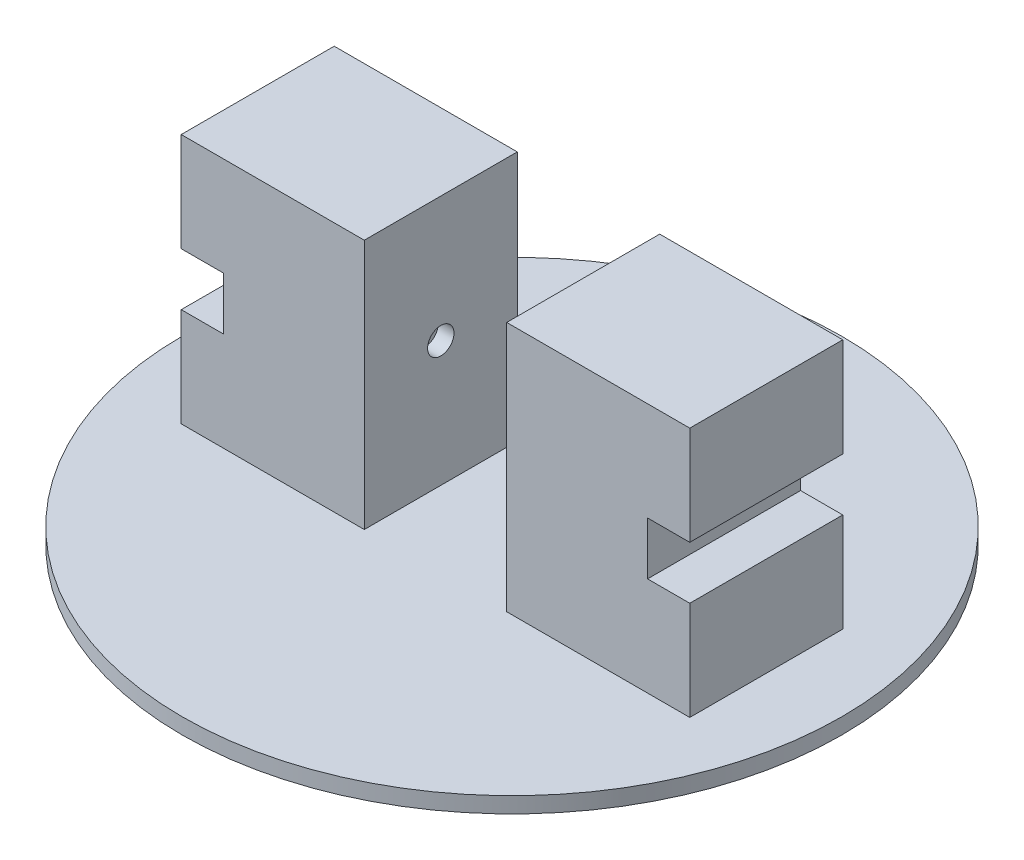
SolidWorks part; units mm, degrees
ref_plane "前视基准面" through (0, 0, 0) normal (0, 0, 1) x (1, 0, 0)
ref_plane "上视基准面" through (0, 0, 0) normal (0, 1, 0) x (1, 0, 0)
ref_plane "右视基准面" through (0, 0, 0) normal (1, 0, 0) x (0, 0, -1)
sketch "草图1" plane through (0, 0, 0) normal (0, 0, 1) x (1, 0, 0)
  line L1 (0, 0) -> (34.7, 0)
  line L2 (0, 0) -> (0, 47.5)
  line L3 (0, 47.5) -> (34.7, 47.5)
  line L4 (34.7, 0) -> (34.7, 47.5)
  line L5 (-27, 0) -> (-61.7, 0)
  line L6 (-27, 0) -> (-27, 47.5)
  line L7 (-27, 47.5) -> (-61.7, 47.5)
  line L8 (-61.7, 0) -> (-61.7, 47.5)
  dimension "D1" = 34.7
  dimension "D2" = 47.5
  dimension "D3" = 27
extrude "凸台-拉伸1" add sketch "草图1" along normal blind 29
sketch "草图2" plane through (34.7, 0, 0) normal (1, 0, 0) x (0, 0, -1)
  line L0 (-29, 23.75) -> (0, 23.75) construction
  line L1 (-29, 0) -> (-29, 47.5) construction
  line L2 (0, 0) -> (0, 47.5) construction
  line L3 (0, 23.75) -> (-29, 23.75) construction
  line L4 (-29, 28.75) -> (0, 28.75)
  line L5 (-29, 28.75) -> (-29, 18.75)
  line L6 (-29, 18.75) -> (0, 18.75)
  line L7 (0, 28.75) -> (0, 18.75)
  dimension "D1" = 10
extrude "切除-拉伸1" cut sketch "草图2" against normal blind 8
sketch "草图3" plane through (-61.7, 0, 0) normal (-1, 0, 0) x (0, 0, 1)
  line L0 (0, 23.75) -> (29, 23.75) construction
  line L1 (0, 47.5) -> (0, 0) construction
  line L2 (29, 47.5) -> (29, 0) construction
  line L3 (29, 23.75) -> (0, 23.75) construction
  line L4 (0, 28.75) -> (29, 28.75)
  line L5 (0, 28.75) -> (0, 18.75)
  line L6 (0, 18.75) -> (29, 18.75)
  line L7 (29, 28.75) -> (29, 18.75)
  dimension "D1" = 10
extrude "切除-拉伸2" cut sketch "草图3" against normal blind 8
sketch "草图4" plane through (0, 0, 0) normal (0, -1, 0) x (1, 0, 0)
  line L0 (-27, 14.5) -> (0, 14.5) construction
  line L1 (-27, 29) -> (-27, 0) construction
  line L2 (0, 29) -> (0, 0) construction
  line L3 (-13.5, 14.5) -> (-13.5, 33.9219) construction
  circle A0 centre (-13.5, 14.5) radius 62.5
  dimension "D1" = 125
extrude "凸台-拉伸2" add sketch "草图4" along normal blind 3
sketch "草图5" plane through (-27, 0, 0) normal (1, 0, 0) x (0, 0, -1)
  line L0 (-14.5, 47.5) -> (-14.5, 0) construction
  line L1 (-29, 47.5) -> (0, 47.5) construction
  line L2 (48, 0) -> (-77, 0) construction
  line L3 (0, 23.75) -> (-29, 23.75) construction
  line L4 (0, 18.75) -> (0, 28.75) construction
  line L5 (-29, 28.75) -> (-29, 18.75) construction
  circle A0 centre (-14.5, 23.75) radius 2.5
  dimension "D1" = 5
extrude "切除-拉伸3" cut sketch "草图5" against normal blind 3 and the other way blind 22
sketch "草图6" plane through (0, 0, 0) normal (-1, 0, 0) x (0, 0, 1)
  line L0 (14.5, 47.5) -> (14.5, 6.5115) construction
  line L1 (29, 47.5) -> (0, 47.5) construction
  line L2 (29, 23.75) -> (6.0356, 23.75)
  line L3 (29, 18.75) -> (29, 28.75) construction
  circle A0 centre (14.5, 23.75) radius 2.5
  dimension "D1" = 5
extrude "切除-拉伸4" cut sketch "草图6" against normal blind 3 contours L2 L0 A0 | L0 L2 A0 | L0 A0 L2 | A0 L0 L2
